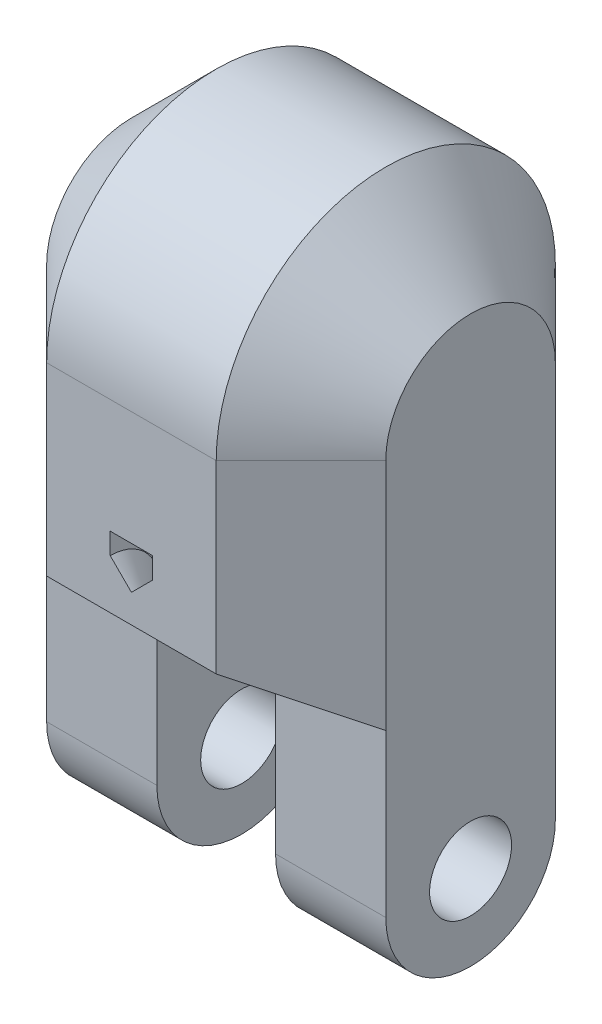
SolidWorks part; units mm, degrees
ref_plane "Front Plane" through (0, 0, 0) normal (0, 0, 1) x (1, 0, 0)
ref_plane "Top Plane" through (0, 0, 0) normal (0, 1, 0) x (1, 0, 0)
ref_plane "Right Plane" through (0, 0, 0) normal (1, 0, 0) x (0, 0, -1)
sketch "Sketch2" plane through (0, 0, 0) normal (0, 1, 0) x (1, 0, 0)
  line L0 (-3, 6) -> (3, 6)
  line L1 (3, 6) -> (6, 3)
  line L2 (6, 3) -> (6, -3)
  line L3 (6, -3) -> (3, -6)
  line L4 (3, -6) -> (-3, -6)
  line L5 (-3, -6) -> (-6, -3)
  line L6 (-6, -3) -> (-6, 3)
  line L7 (-6, 3) -> (-3, 6)
  point P2 (0, -6)
  point P9 (0, 6)
  point P12 (-6, 0)
  point P13 (6, 0)
  dimension "D1" = 12
  dimension "D2" = 12
  dimension "D3" = 6
  dimension "D4" = 6
  dimension "D5" = 6
extrude "Boss-Extrude1" add sketch "Sketch2" along normal mid plane 10 contours L7 L0 L1 L2 L3 L4 L5 L6
sketch "Sketch22" plane through (0, 0, 0) normal (1, 0, 0) x (0, 0, -1)
  line L0 (0, -5) -> (-6, -5)
  line L1 (3, -5) -> (-3, -5) construction
  line L2 (-6, -5) -> (-6, -1.5359)
  line L3 (-6, 5) -> (-6, -5) construction
  line L4 (-6, -1.5359) -> (0, -5)
  dimension "D1" = 30
extrude "Cut-Extrude8" cut sketch "Sketch22" against normal through all both and the other way through all
sketch "Sketch23" plane through (0, 5, 0) normal (0, 1, 0) x (1, 0, 0)
  line L0 (-6, 0) -> (-6, 3)
  line L1 (-6, -3) -> (-6, 3) construction
  line L2 (-6, 3) -> (-3, 6)
  line L3 (-3, 6) -> (3, 6)
  line L4 (3, 6) -> (6, 3)
  line L5 (6, 3) -> (6, 0)
  line L6 (6, 3) -> (6, -3) construction
  line L7 (6, 0) -> (-6, 0)
revolve "Revolve1" add sketch "Sketch23" angle 180 about L7
sketch "Sketch24" plane through (0, -5, 0) normal (0, -1, 0) x (1, 0, 0)
  line L1 (-6, -3) -> (-2.1, -3)
  line L2 (-6, -3) -> (-6, 3)
  line L3 (-6, 3) -> (-2.1, 3)
  line L4 (-2.1, -3) -> (-2.1, 3)
  dimension "D1" = 3.9
extrude "Boss-Extrude2" add sketch "Sketch24" along normal mid plane 8
sketch "Sketch25" plane through (0, -9, 0) normal (0, -1, 0) x (1, 0, 0)
  line L0 (-6, 3) -> (-6, -3) construction
  line L2 (-6, 0) -> (-6, 3)
  line L3 (-6, 3) -> (-2.1, 3)
  line L4 (-2.1, 0) -> (-2.1, 3)
  line L5 (-6, 0) -> (-2.1, 0)
revolve "Revolve2" add sketch "Sketch25" angle 180 about L5
sketch "Sketch26" plane through (-6, 0, 0) normal (-1, 0, 0) x (0, 0, 1)
  line L0 (-3, -9) -> (3, -9) construction
  circle A0 centre (0, -9) radius 1.45
  dimension "D1" = 2.9
extrude "Cut-Extrude9" cut sketch "Sketch26" against normal through all both and the other way through all
mirror "Mirror1" about plane through (0, 0, 0) normal (1, 0, 0) of "Revolve2", "Cut-Extrude9", "Boss-Extrude2"
sketch "Sketch30" plane through (0, -3.75, 2.1651) normal (0, -0.866, 0.5) x (1, 0, 0)
  line L0 (0, 3.4282) -> (-0.75, 2.6782)
  line L1 (-0.75, 2.6782) -> (-0.75, 1.9282)
  line L2 (-0.75, 1.9282) -> (0.75, 1.9282)
  line L3 (0.75, 1.9282) -> (0.75, 2.6782)
  line L4 (0.75, 2.6782) -> (0, 3.4282)
  line L5 (-3, 4.4282) -> (3, 4.4282) construction
  point P10 (0, 4.4282)
  dimension "D1" = 135
  dimension "D2" = 0.75
  dimension "D3" = 1.5
  dimension "D4" = 1
revolve "Cut-Revolve1" cut sketch "Sketch30" angle 360 about axis through (-6, -1.5359, 6) along (1, 0, 0)
sketch "Sketch34" plane through (0, -5, 0) normal (0, -1, 0) x (1, 0, 0)
  line L0 (-6, -3) -> (-2.1, -3)
  line L1 (-2.1, -3) -> (2.1, -3)
  line L2 (2.1, -3) -> (6, -3)
  line L3 (6, -3) -> (3, -6)
  line L4 (3, -6) -> (-3, -6)
  line L5 (-3, -6) -> (-6, -3)
extrude "Boss-Extrude4" add sketch "Sketch34" along normal blind 3.7
sketch "Sketch35" plane through (0, -8.7, 0) normal (0, -1, 0) x (1, 0, 0)
  line L0 (0, -3.5) -> (-0.75, -4.25)
  line L1 (-0.75, -4.25) -> (-0.75, -5)
  line L2 (-0.75, -5) -> (0.75, -5)
  line L3 (0.75, -5) -> (0.75, -4.25)
  line L4 (0.75, -4.25) -> (0, -3.5)
  line L5 (-3, -6) -> (3, -6) construction
  dimension "D1" = 1.5
  dimension "D2" = 1.5
  dimension "D3" = 1
  dimension "D4" = 135
revolve "Cut-Revolve3" cut sketch "Sketch35" angle 360 about axis through (3, -8.7, -6) along (1, 0, 0)
